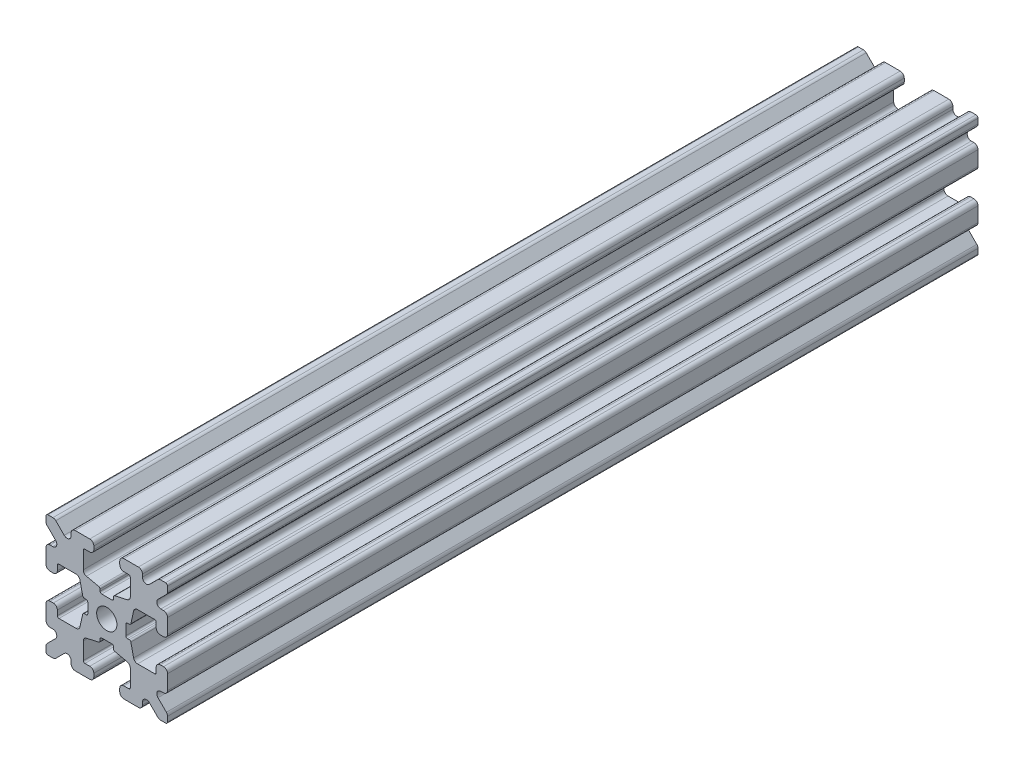
SolidWorks part; units mm, degrees
ref_plane "Front Plane" through (0, 0, 0) normal (0, 0, 1) x (1, 0, 0)
ref_plane "Top Plane" through (0, 0, 0) normal (0, 1, 0) x (1, 0, 0)
ref_plane "Right Plane" through (0, 0, 0) normal (1, 0, 0) x (0, 0, -1)
sketch "Sketch1" plane through (0, 0, 0) normal (0, 0, 1) x (1, 0, 0)
  line L1 (-7.5, -7.5) -> (7.5, -7.5)
  line L2 (-7.5, -7.5) -> (-7.5, 7.5)
  line L3 (-7.5, 7.5) -> (7.5, 7.5)
  line L4 (7.5, -7.5) -> (7.5, 7.5)
  line L5 (-7.5, -7.5) -> (7.5, 7.5) construction
  line L6 (-7.5, 7.5) -> (7.5, -7.5) construction
  circle A0 centre (0, 0) radius 1.25
  point P0 (0, 0)
  dimension "D2" = 2.5
  dimension "D1" = 15
extrude "Boss-Extrude1" add sketch "Sketch1" along normal mid plane 100
fillet "Fillet1" radius 0.25 4 edges at (7.5, -7.5, 0) (-7.5, -7.5, 0) (7.5, 7.5, 0) (-7.5, 7.5, 0)
sketch "Sketch2" plane through (0, 0, 50) normal (0, 0, 1) x (1, 0, 0)
  line L0 (-7.5, 7.25) -> (-7.5, -7.25) construction
  line L1 (-7.5, 1.6) -> (-6.1, 1.6)
  line L2 (-7.5, 1.6) -> (-7.5, -1.6)
  line L3 (-7.5, -1.6) -> (-6.1, -1.6)
  line L4 (-6.1, 1.6) -> (-6.1, 2.9)
  line L5 (0, 0) -> (-12.1036, 0) construction
  line L6 (-6.1, -2.9) -> (-3.4, -2.9)
  line L7 (0, 0) -> (-7.25, 7.25) construction
  line L8 (-6.1, 2.9) -> (-3.4, 2.9)
  line L9 (-3.4, -2.9) -> (-3.4, 2.9)
  line L10 (55, 0) -> (-55, 0) construction
  line L11 (-6.1, -2.9) -> (-6.1, -1.6)
  line L12 (2.9, 6.1) -> (1.6, 6.1)
  line L13 (2.9, 3.4) -> (-2.9, 3.4)
  line L14 (-2.9, 6.1) -> (-2.9, 3.4)
  line L15 (2.9, 6.1) -> (2.9, 3.4)
  line L16 (-1.6, 6.1) -> (-2.9, 6.1)
  line L17 (1.6, 7.5) -> (1.6, 6.1)
  line L18 (-1.6, 7.5) -> (1.6, 7.5)
  line L19 (-1.6, 7.5) -> (-1.6, 6.1)
  line L20 (-1.6, -7.5) -> (-1.6, -6.1)
  line L21 (-1.6, -7.5) -> (1.6, -7.5)
  line L22 (1.6, -7.5) -> (1.6, -6.1)
  line L23 (-1.6, -6.1) -> (-2.9, -6.1)
  line L24 (2.9, -6.1) -> (2.9, -3.4)
  line L25 (-2.9, -6.1) -> (-2.9, -3.4)
  line L26 (2.9, -3.4) -> (-2.9, -3.4)
  line L27 (2.9, -6.1) -> (1.6, -6.1)
  line L28 (6.1, -2.9) -> (6.1, -1.6)
  line L29 (3.4, -2.9) -> (3.4, 2.9)
  line L30 (6.1, 2.9) -> (3.4, 2.9)
  line L31 (6.1, -2.9) -> (3.4, -2.9)
  line L32 (6.1, 1.6) -> (6.1, 2.9)
  line L33 (7.5, -1.6) -> (6.1, -1.6)
  line L34 (7.5, 1.6) -> (7.5, -1.6)
  line L35 (7.5, 1.6) -> (6.1, 1.6)
  dimension "D1" = 3.2
  dimension "D2" = 5.8
  dimension "D3" = 1.4
  dimension "D4" = 2.7
extrude "Cut-Extrude1" cut sketch "Sketch2" against normal through all
sketch "Sketch4" plane through (0, 0, 50) normal (0, 0, 1) x (1, 0, 0)
  line L0 (-3.4, 2.9) -> (-2.75, 0)
  line L1 (55, 0) -> (-55, 0) construction
  line L2 (-2.75, 0) -> (-3.4, -2.9)
  line L3 (-3.4, -2.9) -> (-3.4, 2.9) construction
  line L4 (-3.4, 2.9) -> (-3.4, -2.9)
  line L5 (-2.9, 3.4) -> (0, 2.75)
  line L6 (0, 2.75) -> (2.9, 3.4)
  line L7 (2.9, 3.4) -> (-2.9, 3.4)
  line L8 (3.4, 2.9) -> (2.75, 0)
  line L9 (2.75, 0) -> (3.4, -2.9)
  line L10 (3.4, -2.9) -> (3.4, 2.9)
  line L11 (-2.9, -3.4) -> (0, -2.75)
  line L12 (0, -2.75) -> (2.9, -3.4)
  line L13 (2.9, -3.4) -> (-2.9, -3.4)
  circle A2 centre (0, 0) radius 2.75
  circle A3 centre (0, 0) radius 2.75 construction
  dimension "D1" = 1.5
extrude "Cut-Extrude3" cut sketch "Sketch4" against normal through all
fillet "Fillet3" radius 0.5 16 edges at (-6.1, -1.6, 0) (-7.5, -1.6, 0) (-6.1, 1.6, 0) (-7.5, 1.6, 0) (-1.6, -7.5, 0) (-1.6, -6.1, 0) (1.6, -7.5, 0) (1.6, -6.1, 0) (6.1, -1.6, 0) (7.5, -1.6, 0) (7.5, 1.6, 0) (6.1, 1.6, 0) (1.6, 7.5, 0) (1.6, 6.1, 0) (-1.6, 7.5, 0) (-1.6, 6.1, 0)
fillet "Fillet4" radius 0.5 8 edges at (-3.4, 2.9, 0) (-3.4, -2.9, 0) (2.9, -3.4, 0) (-2.9, -3.4, 0) (3.4, -2.9, 0) (3.4, 2.9, 0) (-2.9, 3.4, 0) (2.9, 3.4, 0)
fillet "Fillet5" radius 3 4 edges at (0, -2.75, 0) (2.75, 0, 0) (-2.75, 0, 0) (0, 2.75, 0)
fillet "Fillet6" radius 0.2 8 edges at (-2.9, -6.1, 0) (2.9, -6.1, 0) (6.1, -2.9, 0) (6.1, 2.9, 0) (2.9, 6.1, 0) (-2.9, 6.1, 0) (-6.1, -2.9, 0) (-6.1, 2.9, 0)
sketch "Sketch5" plane through (0, 0, 50) normal (0, 0, 1) x (1, 0, 0)
  line L0 (0, 0) -> (-7.25, 7.25) construction
  line L1 (-7.5, 6.4393) -> (-5.4607, 4.4)
  line L2 (-6.4393, 7.5) -> (-4.4, 5.4607)
  line L3 (-7.5, 4.4) -> (-5.4607, 4.4)
  line L4 (-3.8003, 2.9) -> (-5.9, 2.9) construction
  line L5 (0, 0) -> (-12.1819, 0) construction
  line L6 (-4.4, 7.5) -> (-4.4, 5.4607)
  line L7 (-2.9, 5.9) -> (-2.9, 3.8003) construction
  line L8 (-7.5, 6.4393) -> (-7.5, 4.4)
  line L9 (-7.5, 7.25) -> (-7.5, 2.1) construction
  line L10 (2.1, -7.5) -> (7.25, -7.5) construction
  line L11 (7.5, -7.25) -> (7.5, -2.1) construction
  line L12 (7.25, 7.5) -> (2.1, 7.5) construction
  line L13 (-2.1, 7.5) -> (-7.25, 7.5) construction
  line L14 (-4.4, 7.5) -> (-6.4393, 7.5)
  line L16 (55, 0) -> (-55, 0) construction
  line L17 (0, 0) -> (0, 10.993) construction
  line L18 (0, -54.6431) -> (0, 54.6431) construction
  line L20 (4.4, 7.5) -> (6.4393, 7.5)
  line L22 (7.5, 6.4393) -> (7.5, 4.4)
  line L23 (4.4, 7.5) -> (4.4, 5.4607)
  line L24 (7.5, 4.4) -> (5.4607, 4.4)
  line L25 (6.4393, 7.5) -> (4.4, 5.4607)
  line L26 (7.5, 6.4393) -> (5.4607, 4.4)
  line L27 (7.5, -6.4393) -> (5.4607, -4.4)
  line L28 (6.4393, -7.5) -> (4.4, -5.4607)
  line L29 (7.5, -4.4) -> (5.4607, -4.4)
  line L30 (4.4, -7.5) -> (4.4, -5.4607)
  line L31 (7.5, -6.4393) -> (7.5, -4.4)
  line L33 (4.4, -7.5) -> (6.4393, -7.5)
  line L36 (-4.4, -7.5) -> (-6.4393, -7.5)
  line L38 (-7.5, -6.4393) -> (-7.5, -4.4)
  line L39 (-4.4, -7.5) -> (-4.4, -5.4607)
  line L40 (-7.5, -4.4) -> (-5.4607, -4.4)
  line L41 (-6.4393, -7.5) -> (-4.4, -5.4607)
  line L42 (-7.5, -6.4393) -> (-5.4607, -4.4)
  dimension "D1" = 1.5
  dimension "D2" = 1.5
  dimension "D3" = 1.5
extrude "Cut-Extrude4" cut sketch "Sketch5" against normal through all
fillet "Fillet8" radius 0.5 24 edges at (-5.4607, 4.4, 0) (-7.5, 4.4, 0) (-5.4607, -4.4, 0) (-7.5, -4.4, 0) (-4.4, -7.5, 0) (-4.4, -5.4607, 0) (4.4, -7.5, 0) (4.4, -5.4607, 0) (5.4607, -4.4, 0) (7.5, -4.4, 0) (7.5, 4.4, 0) (5.4607, 4.4, 0) (4.4, 5.4607, 0) (4.4, 7.5, 0) (-4.4, 5.4607, 0) (-4.4, 7.5, 0) (-6.4393, 7.5, 0) (-7.5, 6.4393, 0) (6.4393, 7.5, 0) (7.5, 6.4393, 0) (6.4393, -7.5, 0) (7.5, -6.4393, 0) (-6.4393, -7.5, 0) (-7.5, -6.4393, 0)
sketch "Sketch6" plane through (0, 0, 50) normal (0, 0, 1) x (1, 0, 0)
  line L0 (0, 0) -> (0, 11.013) construction
  line L1 (0.6561, 2.8971) -> (2.1235, 2.8971) construction
  line L2 (0, -54.6431) -> (0, 54.6431) construction
  line L3 (0, 0) -> (7.25, 7.25) construction
  line L4 (7.5, 0.8255) -> (7.5, -0.8255)
  line L5 (2.3471, 0.8255) -> (7.5, 0.8255)
  line L6 (0, 0) -> (12.4016, 0) construction
  line L7 (0.8255, -7.5) -> (-0.8255, -7.5)
  line L8 (2.3471, -0.8255) -> (2.3471, 0.8255)
  line L9 (0.8255, -2.3471) -> (0.8255, -7.5)
  line L10 (7.5, -0.8255) -> (2.3471, -0.8255)
  line L11 (-7.5, -0.8255) -> (-2.3471, -0.8255)
  line L12 (-2.3471, -0.8255) -> (-2.3471, 0.8255)
  line L13 (-0.8255, -2.3471) -> (0.8255, -2.3471)
  line L14 (-0.8255, 7.5) -> (-0.8255, 2.3471)
  line L15 (-0.8255, 2.3471) -> (0.8255, 2.3471)
  line L16 (-0.8255, -7.5) -> (-0.8255, -2.3471)
  line L17 (0.8255, 2.3471) -> (0.8255, 7.5)
  line L18 (0.8255, 7.5) -> (-0.8255, 7.5)
  line L19 (3.9, 7.5) -> (2.1, 7.5) construction
  line L20 (-2.3471, 0.8255) -> (-7.5, 0.8255)
  line L21 (-7.5, 0.8255) -> (-7.5, -0.8255)
  point P5 (0, -2.5973)
  point P7 (0, 2.5973)
  dimension "D3" = 0.55
  dimension "D1" = 1.651
extrude "Cut-Extrude5" cut sketch "Sketch6" against normal through all
fillet "Fillet10" radius 0.2 16 edges at (-2.935, 0.8255, 0) (-2.935, -0.8255, 0) (2.935, -0.8255, 0) (2.935, 0.8255, 0) (0.8255, 2.935, 0) (-0.8255, 2.935, 0) (-2.3471, 0.8255, 0) (-2.3471, -0.8255, 0) (0.8255, 2.3471, 0) (-0.8255, 2.3471, 0) (2.3471, 0.8255, 0) (2.3471, -0.8255, 0) (0.8255, -2.935, 0) (0.8255, -2.3471, 0) (-0.8255, -2.3471, 0) (-0.8255, -2.935, 0)
